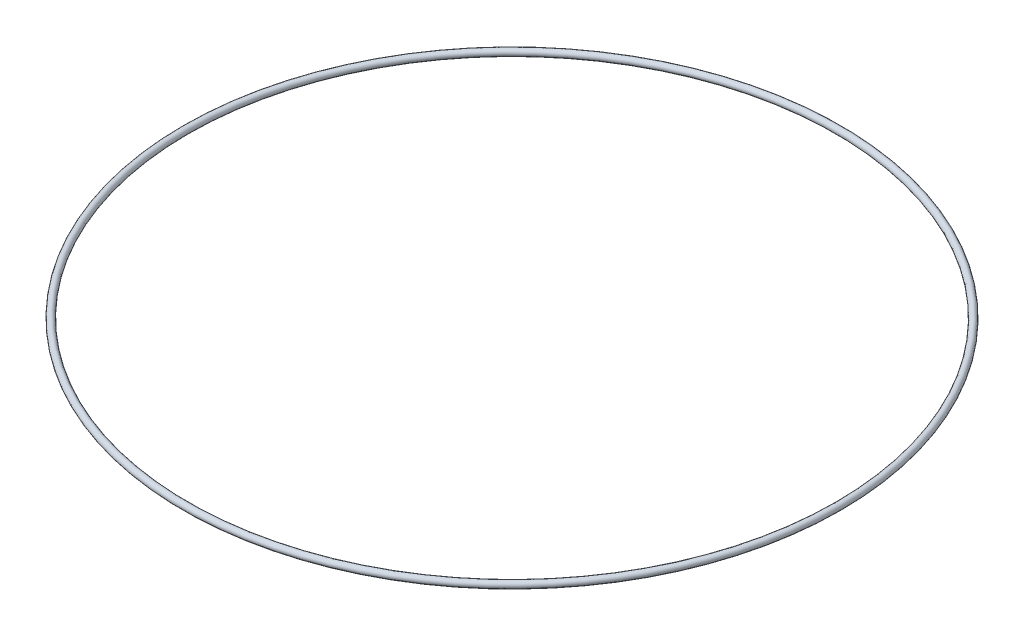
SolidWorks part; units mm, degrees
ref_plane "Front Plane" through (0, 0, 0) normal (0, 0, 1) x (1, 0, 0)
ref_plane "Top Plane" through (0, 0, 0) normal (0, 1, 0) x (1, 0, 0)
ref_plane "Right Plane" through (0, 0, 0) normal (1, 0, 0) x (0, 0, -1)
sketch "Sketch1" plane through (0, -224.794, 0) normal (0, 0, 1) x (1, 0, 0)
  line L0 (0, 372.6851) -> (0, -167.4524) construction
  circle A0 centre (-914.4, 0) radius 9.525
  circle A1 centre (-914.4, 0) radius 7.62
  point P6 (0, 0)
  dimension "D1" = 19.05
  dimension "D2" = 1.905
  dimension "D3" = 914.4
revolve "Revolve1" add sketch "Sketch1" angle 360 about L0
